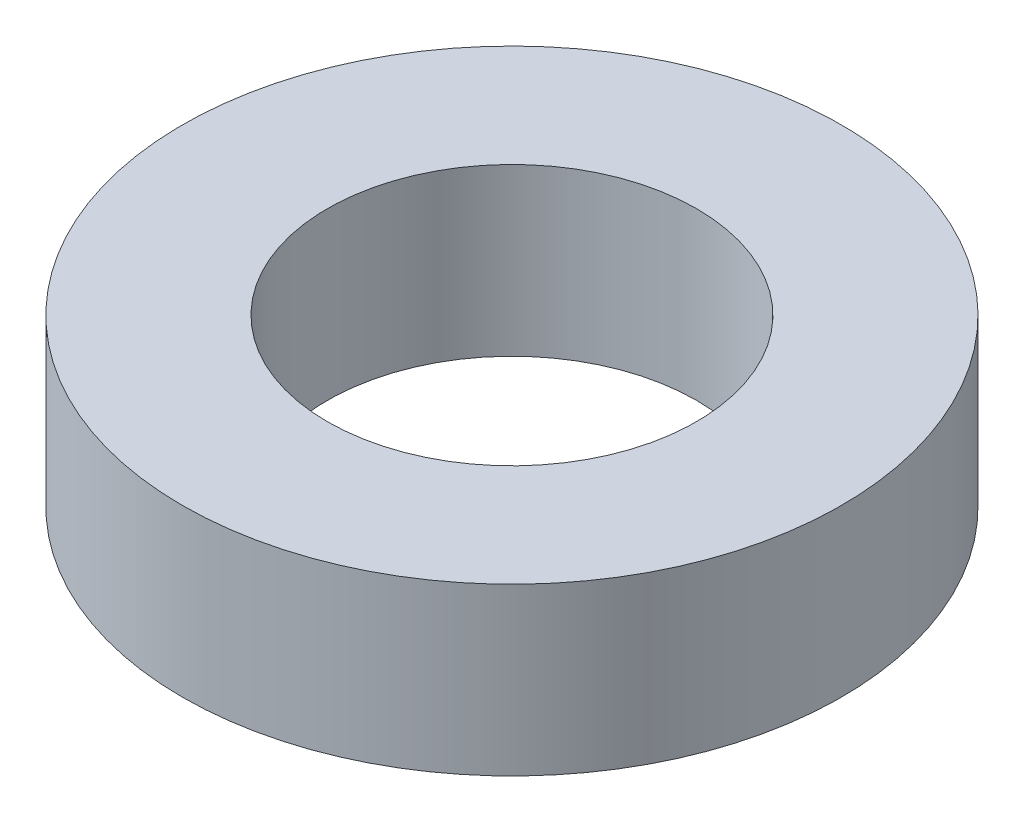
SolidWorks part; units mm, degrees
ref_plane "Front Plane" through (0, 0, 0) normal (0, 0, 1) x (1, 0, 0)
ref_plane "Top Plane" through (0, 0, 0) normal (0, 1, 0) x (1, 0, 0)
ref_plane "Right Plane" through (0, 0, 0) normal (1, 0, 0) x (0, 0, -1)
sketch "Sketch1" plane through (0, 0, 0) normal (0, 1, 0) x (1, 0, 0)
  circle A0 centre (0, 0) radius 3.175
  circle A1 centre (0, 0) radius 1.778
  point P3 (0, 0)
  dimension "D1" = 3.556
  dimension "D2" = 6.35
extrude "Boss-Extrude1" add sketch "Sketch1" along normal blind 1.6
